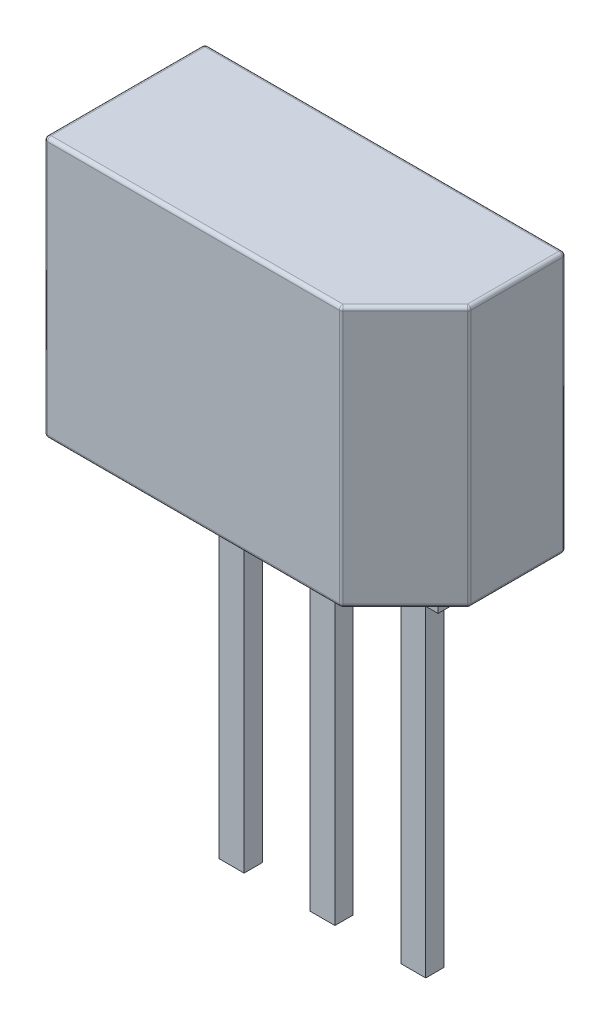
SolidWorks part; units mm, degrees
ref_plane "Ebene vorne" through (0, 0, 0) normal (0, 0, 1) x (1, 0, 0)
ref_plane "Ebene oben" through (0, 0, 0) normal (0, 1, 0) x (1, 0, 0)
ref_plane "Ebene rechts" through (0, 0, 0) normal (1, 0, 0) x (0, 0, -1)
sketch "Skizze1" plane through (0, 0, 0) normal (0, 1, 0) x (1, 0, 0)
  line L1 (-5.05, -2.25) -> (5.05, -2.25)
  line L2 (-5.05, -2.25) -> (-5.05, 2.25)
  line L3 (-5.05, 2.25) -> (5.05, 2.25)
  line L4 (5.05, -2.25) -> (5.05, 2.25)
  line L5 (-5.05, -2.25) -> (5.05, 2.25) construction
  line L6 (-5.05, 2.25) -> (5.05, -2.25) construction
  point P0 (0, 0)
extrude "Aufsatz-Linear austragen1" add sketch "Skizze1" along normal blind 7.3
chamfer "Fase2" distance 1.8 1 edges at (5.05, 3.65, 2.25)
ref_plane "Ebene2" through (0, 0, -0.745) normal (0, 0, 1) x (1, 0, 0)
sketch "Skizze3" plane through (0, 0, -0.745) normal (0, 0, 1) x (1, 0, 0)
  line L0 (0, 0) -> (-0.6982, 0)
  line L1 (-0.6982, 0) -> (-0.6982, -1.5022)
  line L2 (-0.6982, -1.5022) -> (-0.3491, -1.5022)
  line L3 (-0.3491, -1.5022) -> (-0.3491, -10.5054)
  line L4 (-0.3491, -10.5054) -> (0.3466, -10.5054)
  line L5 (0.3466, -10.5054) -> (0.3466, -1.5022)
  line L6 (0.3466, -1.5022) -> (0.6921, -1.5022)
  line L7 (0.6921, -1.5022) -> (0.6921, 0)
  line L8 (0.6921, 0) -> (0, 0)
extrude "Aufsatz-Linear austragen2" add sketch "Skizze3" along normal blind 0.255 and the other way blind 0.255
pattern_linear "Lineares Muster1" count 2 spacing 2.54 along (1, 0, 0) count 2 spacing 2.54 along (-1, 0, 0) of "Aufsatz-Linear austragen2"
fillet "Verrundung1" radius 0.1 27 edges at (5.05, 3.65, -2.25) (-5.05, 3.65, -2.25) (-5.05, 3.65, 2.25) (-5.05, 7.3, 0) (0, 7.3, -2.25) (5.05, 7.3, -0.9) (-0.9, 7.3, 2.25) (2.5369, 0, -0.49) (1.8418, 0, -0.745) (2.5369, 0, -1) (3.2321, 0, -0.745) (-0.0031, 0, -0.49) (-0.6982, 0, -0.745) (-0.0031, 0, -1) (0.6921, 0, -0.745) (0, 0, -2.25) (-5.05, 0, 0) (-0.9, 0, 2.25) (5.05, 0, -0.9) (-2.5431, 0, -0.49) (-3.2382, 0, -0.745) (-2.5431, 0, -1) (-1.8479, 0, -0.745) (5.05, 3.65, 0.45) (4.15, 0, 1.35) (3.25, 3.65, 2.25) (4.15, 7.3, 1.35)
